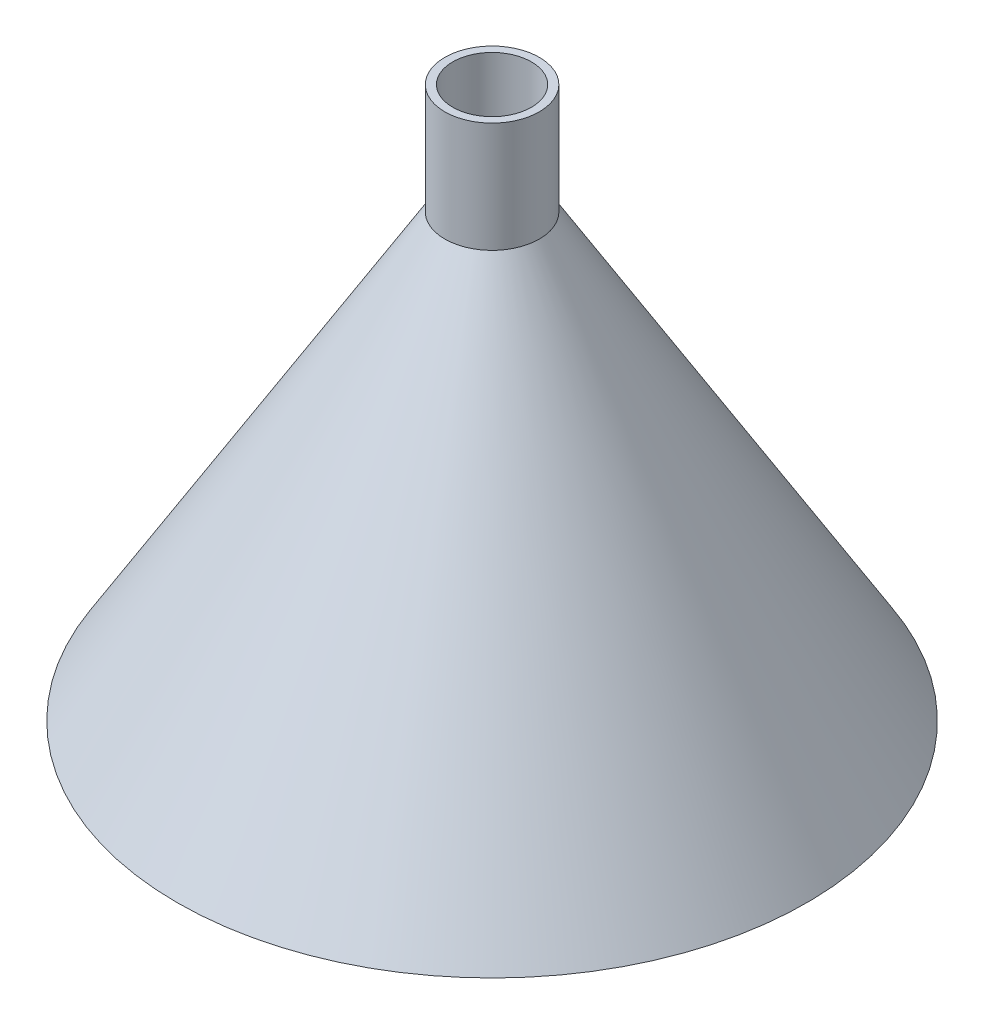
SolidWorks part; units mm, degrees
material "ABS"
ref_plane "Front Plane" through (0, 0, 0) normal (0, 0, 1) x (1, 0, 0)
ref_plane "Top Plane" through (0, 0, 0) normal (0, 1, 0) x (1, 0, 0)
ref_plane "Right Plane" through (0, 0, 0) normal (1, 0, 0) x (0, 0, -1)
sketch "Sketch1" plane through (0, 0, 0) normal (0, 1, 0) x (1, 0, 0)
  circle A0 centre (0, 0) radius 100
  circle A1 centre (0, 0) radius 15
  point P0 (0, 0)
  point P5 (-25.2159, 616.3939)
  point P6 (0, 0)
  dimension "D1" = 200
  dimension "D2" = 30
extrude "Boss-Extrude3" add sketch "Sketch1" along normal blind 140 draft 31.3 contours A0
sketch "Sketch2" plane through (0, 0, 0) normal (0, -1, 0) x (1, 0, 0)
  circle A2 centre (0, 0) radius 97.5
  dimension "D1" = 195
extrude "Cut-Extrude1" cut sketch "Sketch2" against normal blind 140 draft 31.3
sketch "Sketch4" plane through (0, 140, 0) normal (0, 1, 0) x (1, 0, 0)
  circle A0 centre (0, 0) radius 15
  circle A1 centre (0, 0) radius 12.3787 construction
  dimension "D1" = 30
extrude "Extrude-Thin1" add sketch "Sketch4" along normal blind 35 thin thin type one direction reverse wall 2.5
